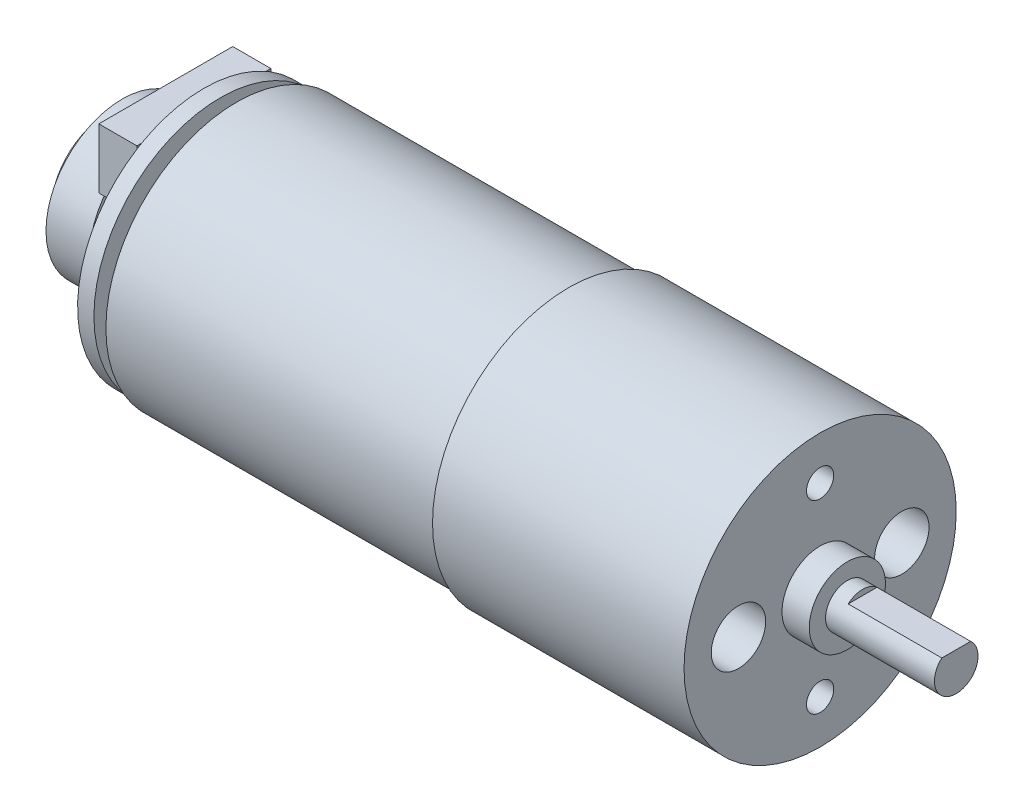
SolidWorks part; units mm, degrees
ref_plane "Спереди" through (0, 0, 0) normal (0, 0, 1) x (1, 0, 0)
ref_plane "Сверху" through (0, 0, 0) normal (0, 1, 0) x (1, 0, 0)
ref_plane "Справа" through (0, 0, 0) normal (1, 0, 0) x (0, 0, -1)
sketch "Эскиз2" plane through (0, 0, 0) normal (1, 0, 0) x (0, 0, -1)
  circle A0 centre (0, 0) radius 12.5
  dimension "D1" = 25
sketch "Эскиз4" plane through (0, 0, 0) normal (1, 0, 0) x (0, 0, -1)
  circle A0 centre (0, 0) radius 12.5
  dimension "D1" = 25
extrude "тело двигателя" add sketch "Эскиз4" along normal blind 53.6
sketch "Эскиз5" plane through (53.6, 0, 0) normal (1, 0, 0) x (0, 0, -1)
  circle A0 centre (0, 0) radius 2
  dimension "D1" = 4
sketch "Эскиз6" plane through (53.6, 0, 0) normal (1, 0, 0) x (0, 0, -1)
  circle A0 centre (0, 0) radius 2
  dimension "D1" = 4
extrude "вал" add sketch "Эскиз6" along normal blind 12.5
ref_plane "Плоскость1" through (0, 2, 0) normal (0, 1, 0) x (1, 0, 0)
sketch "Эскиз7" plane through (0, 2, 0) normal (0, 1, 0) x (1, 0, 0)
  line L0 (53.6, -12.5) -> (53.6, 12.5) construction
  line L1 (53.6, 3.8012) -> (68.8044, 3.8012)
  line L2 (53.6, 3.8012) -> (53.6, -4.7425)
  line L3 (53.6, -4.7425) -> (68.8044, -4.7425)
  line L4 (68.8044, 3.8012) -> (68.8044, -4.7425)
  dimension "D1" = 15.2044
  dimension "D2" = 8.5437
  dimension "D3" = 4.7425
sketch "Эскиз8" plane through (0, 2, 0) normal (0, 1, 0) x (1, 0, 0)
  line L0 (57.5004, 3.8012) -> (68.8044, 3.8012)
  line L1 (57.5004, 3.8012) -> (57.5004, -4.7425)
  line L2 (57.5004, -4.7425) -> (68.8044, -4.7425)
  line L3 (68.8044, 3.8012) -> (68.8044, -4.7425)
  line L4 (53.6, -12.5) -> (53.6, 12.5) construction
  dimension "D1" = 11.304
  dimension "D2" = 8.5437
  dimension "D3" = 15.2044
extrude "фаска" cut sketch "Эскиз8" against normal blind 0.5
sketch "Эскиз9" plane through (53.6, 0, 0) normal (1, 0, 0) x (0, 0, -1)
  circle A0 centre (0, 0) radius 3.5
  dimension "D1" = 7
sketch "Эскиз10" plane through (53.6, 0, 0) normal (1, 0, 0) x (0, 0, -1)
  circle A0 centre (0, 0) radius 3.5
  dimension "D1" = 7
extrude "золотое кольцо" add sketch "Эскиз10" along normal blind 2.5
sketch "Эскиз11" plane through (53.6, 0, 0) normal (1, 0, 0) x (0, 0, -1)
  circle A0 centre (0, 8.5) radius 0.75
  circle A1 centre (0, -8.5) radius 0.75
  point P6 (0, 8.5)
  point P7 (0, -8.5)
  point P8 (0, -8.5)
  point P9 (-20.4145, 0.2984)
  dimension "D1" = 1.5
  dimension "D2" = 1.5
  dimension "D3" = 8.5
  dimension "D4" = 8.5
  dimension "D5" = 17
sketch "Эскиз14" plane through (53.6, 0, 0) normal (1, 0, 0) x (0, 0, -1)
  circle A0 centre (0, 8.5) radius 1.25
  circle A1 centre (0, -8.5) radius 1.25
  point P3 (0, 8.5)
  point P4 (0, -8.5)
  point P5 (0, -8.5)
  dimension "D1" = 2.5
  dimension "D2" = 2.5
  dimension "D3" = 17
extrude "крпежные отверстия" cut sketch "Эскиз14" against normal blind 15
sketch "Эскиз16" plane through (53.6, 0, 0) normal (1, 0, 0) x (0, 0, -1)
  circle A0 centre (-7.5, 0) radius 2.5
  circle A1 centre (7.5, 0) radius 2.5
  dimension "D1" = 5
  dimension "D2" = 5
extrude "отверстия с винтами" cut sketch "Эскиз16" against normal blind 5
sketch "Эскиз17" plane through (0, 0, 0) normal (-1, 0, 0) x (0, 0, 1)
  circle A0 centre (0, 0) radius 3.2
  dimension "D1" = 6.4
sketch "Эскиз18" plane through (0, 0, 0) normal (-1, 0, 0) x (0, 0, 1)
  circle A0 centre (0, 0) radius 3.2
  dimension "D1" = 6.4
extrude "выступ" add sketch "Эскиз18" along normal blind 1.5
sketch "Эскиз20" plane through (-1.5, 0, 0) normal (-1, 0, 0) x (0, 0, 1)
  circle A0 centre (0, 0) radius 11.6
  dimension "D1" = 23.2
sketch "Эскиз21" plane through (-1.5, 0, 0) normal (-1, 0, 0) x (0, 0, 1)
  circle A0 centre (0, 0) radius 11.6
  dimension "D1" = 23.2
extrude "диск-плата" add sketch "Эскиз21" along normal blind 1.5
sketch "Эскиз22" plane through (-3, 0, 0) normal (-1, 0, 0) x (0, 0, 1)
  line L0 (0, 0) -> (0, 7.35) construction
  line L2 (-6.15, 10.1) -> (6.15, 10.1)
  line L3 (-6.15, 10.1) -> (-6.15, 4.6)
  line L4 (-6.15, 4.6) -> (6.15, 4.6)
  line L5 (6.15, 10.1) -> (6.15, 4.6)
  line L6 (-6.15, 10.1) -> (6.15, 4.6) construction
  line L7 (-6.15, 4.6) -> (6.15, 10.1) construction
  dimension "D1" = 12.3
  dimension "D2" = 5.5
  dimension "D3" = 7.35
sketch "Эскиз23" plane through (-3, 0, 0) normal (-1, 0, 0) x (0, 0, 1)
  line L0 (0, 0) -> (0, 7.35) construction
  line L1 (-6.15, 10.1) -> (6.15, 10.1)
  line L2 (-6.15, 10.1) -> (-6.15, 4.6)
  line L3 (-6.15, 4.6) -> (6.15, 4.6)
  line L4 (6.15, 10.1) -> (6.15, 4.6)
  line L5 (-6.15, 10.1) -> (6.15, 4.6) construction
  line L6 (-6.15, 4.6) -> (6.15, 10.1) construction
  dimension "D1" = 12.3
  dimension "D2" = 5.5
  dimension "D3" = 7.35
extrude "разъемы" add sketch "Эскиз23" along normal blind 3.5
sketch "Эскиз24" plane through (-3, 0, 0) normal (-1, 0, 0) x (0, 0, 1)
  line L0 (0, 0) -> (0, -7.6) construction
  line L2 (-2.55, -6.6) -> (2.55, -6.6)
  line L3 (-2.55, -6.6) -> (-2.55, -8.6)
  line L4 (-2.55, -8.6) -> (2.55, -8.6)
  line L5 (2.55, -6.6) -> (2.55, -8.6)
  line L6 (-2.55, -6.6) -> (2.55, -8.6) construction
  line L7 (-2.55, -8.6) -> (2.55, -6.6) construction
  dimension "D1" = 5.1
  dimension "D2" = 2
  dimension "D3" = 7.6
sketch "Эскиз25" plane through (-3, 0, 0) normal (-1, 0, 0) x (0, 0, 1)
  line L1 (-2.55, -7.2) -> (2.55, -7.2)
  line L2 (-2.55, -7.2) -> (-2.55, -9.2)
  line L3 (-2.55, -9.2) -> (2.55, -9.2)
  line L4 (2.55, -7.2) -> (2.55, -9.2)
  line L5 (-2.55, -7.2) -> (2.55, -9.2) construction
  line L6 (-2.55, -9.2) -> (2.55, -7.2) construction
  arc A0 (-6.15, 9.8355) -> (6.15, 9.8355) centre (0, 0) ccw construction
  point P0 (0, -8.2)
  dimension "D1" = 5.1
  dimension "D2" = 2
  dimension "D3" = 8.2
extrude "черная хрень" add sketch "Эскиз25" along normal blind 8
sketch "Эскиз26" plane through (-3, 0, 0) normal (-1, 0, 0) x (0, 0, 1)
  circle A0 centre (0, 0) radius 0.75
  dimension "D1" = 1.5
sketch "Эскиз27" plane through (-3, 0, 0) normal (-1, 0, 0) x (0, 0, 1)
  circle A0 centre (0, 0) radius 0.75
  dimension "D1" = 1.5
extrude "тонкий вал внутри" add sketch "Эскиз27" along normal blind 3.5
sketch "Эскиз28" plane through (-6.5, 0, 0) normal (-1, 0, 0) x (0, 0, 1)
  circle A0 centre (0, 0) radius 7
  dimension "D1" = 14
sketch "Эскиз32" plane through (-6.5, 0, 0) normal (-1, 0, 0) x (0, 0, 1)
  circle A0 centre (0, 0) radius 7
  dimension "D1" = 14
extrude "черный диск" add sketch "Эскиз32" along normal blind 4
sketch "Эскиз33" plane through (-11, 0, 0) normal (-1, 0, 0) x (0, 0, 1)
  circle A0 centre (0, 0) radius 5
  dimension "D1" = 10
extrude "Бобышка-Вытянуть12" add sketch "Эскиз33" along normal blind 1
sketch "Эскиз34" plane through (-10.5, 0, 0) normal (-1, 0, 0) x (0, 0, 1)
  circle A0 centre (0, 0) radius 5
  dimension "D1" = 10
sketch "Эскиз35" plane through (-10.5, 0, 0) normal (-1, 0, 0) x (0, 0, 1)
  circle A0 centre (0, 0) radius 5
  dimension "D1" = 10
extrude "желтый диск" add sketch "Эскиз35" along normal blind 1
sketch "Эскиз36" plane through (-12, 0, 0) normal (-1, 0, 0) x (0, 0, 1)
  circle A0 centre (0, 0) radius 1.5
  dimension "D1" = 3
sketch "Эскиз37" plane through (-12, 0, 0) normal (-1, 0, 0) x (0, 0, 1)
  circle A0 centre (0, 0) radius 1.5
  dimension "D1" = 3
extrude "крепеж желтого диска" cut sketch "Эскиз37" against normal blind 2
sketch "Эскиз39" plane through (0, 0, 0) normal (-1, 0, 0) x (0, 0, 1)
  circle A0 centre (0, 0) radius 12
  dimension "D1" = 24
sketch "Эскиз40" plane through (0, 0, 0) normal (-1, 0, 0) x (0, 0, 1)
  circle A0 centre (0, 0) radius 12
  dimension "D1" = 24
extrude "разница в диаметре" cut sketch "Эскиз40" against normal blind 30.5 flip side to cut
